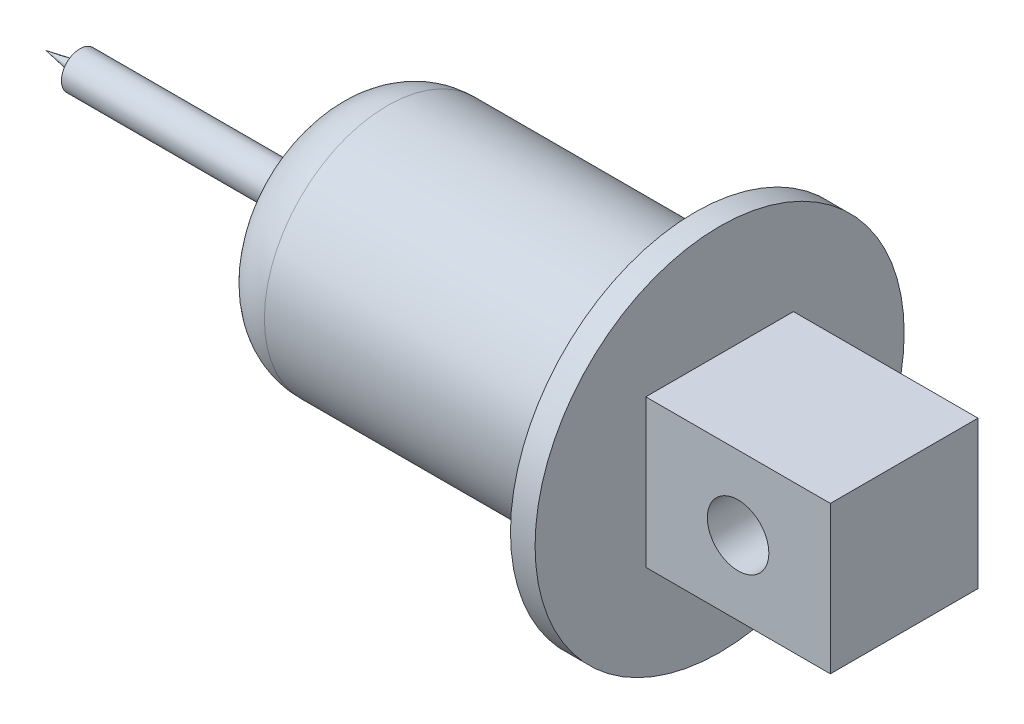
SolidWorks part; units mm, degrees
ref_plane "Ön Düzlem" through (0, 0, 0) normal (0, 0, 1) x (1, 0, 0)
ref_plane "Üst Düzlem" through (0, 0, 0) normal (0, 1, 0) x (1, 0, 0)
ref_plane "Sağ Düzlem" through (0, 0, 0) normal (1, 0, 0) x (0, 0, -1)
sketch "Sketch1" plane through (0, 0, 0) normal (0, 0, 1) x (1, 0, 0)
  circle A0 centre (0, 0) radius 15
  dimension "D1" = 30
extrude "Boss-Extrude1" add sketch "Sketch1" against normal blind 2
sketch "Sketch2" plane through (0, 0, 0) normal (0, 0, 1) x (1, 0, 0)
  line L1 (-6, 6) -> (6, 6)
  line L2 (-6, 6) -> (-6, -6)
  line L3 (-6, -6) -> (6, -6)
  line L4 (6, 6) -> (6, -6)
  line L5 (-6, 6) -> (6, -6) construction
  line L6 (-6, -6) -> (6, 6) construction
  point P0 (0, 0)
  dimension "D1" = 12
  dimension "D2" = 12
extrude "Boss-Extrude2" add sketch "Sketch2" along normal blind 15
sketch "Sketch3" plane through (6, 0, 0) normal (1, 0, 0) x (0, 0, -1)
  circle A0 centre (-7.5, 0) radius 2.5
  dimension "D1" = 5
extrude "Cut-Extrude1" cut sketch "Sketch3" against normal through all
sketch "Sketch4" plane through (0, 0, -2) normal (0, 0, -1) x (-1, 0, 0)
  circle A0 centre (0, 0) radius 10
  dimension "D1" = 20
extrude "Boss-Extrude3" add sketch "Sketch4" along normal blind 30
fillet "Fillet1" radius 5 1 edges at (-10, 0, -32)
sketch "Sketch5" plane through (0, 0, -32) normal (0, 0, -1) x (-1, 0, 0)
  circle A0 centre (0, 0) radius 1.5
  dimension "D1" = 3
extrude "Boss-Extrude4" add sketch "Sketch5" along normal blind 20
sketch "Sketch7" plane through (0, 0, -52) normal (0, 0, -1) x (-1, 0, 0)
  circle A0 centre (0, 0) radius 0.5
  dimension "D1" = 1
ref_plane "Plane2" through (0, 0, -54.75) normal (0, 0, -1) x (-1, 0, 0)
sketch "Sketch12" plane through (0, 0, -54.75) normal (0, 0, -1) x (-1, 0, 0)
  point P0 (0, 0)
loft "Loft2" add profiles "Sketch12", "Sketch7"
sketch "Sketch14" plane through (0, 0, -52) normal (0, 0, -1) x (-1, 0, 0)
  point P0 (0, 0)
move or copy body "Body-Move/Copy1" bodies to move or copy 108 copy no translate (0, 0, 52)
move or copy body "Body-Move/Copy2" bodies to move or copy 109 copy no rotation origin (0, 0, 0) rotation axis (0, 1, 0) rotation angle 90
